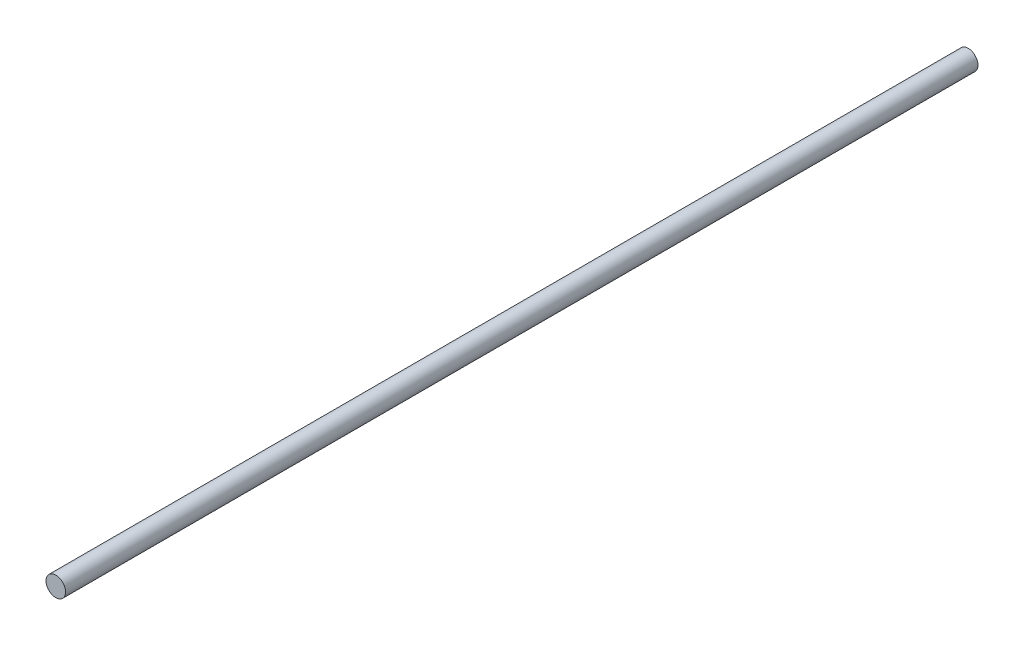
SolidWorks part; units mm, degrees
ref_plane "Front Plane" through (0, 0, 0) normal (0, 0, 1) x (1, 0, 0)
ref_plane "Top Plane" through (0, 0, 0) normal (0, 1, 0) x (1, 0, 0)
ref_plane "Right Plane" through (0, 0, 0) normal (1, 0, 0) x (0, 0, -1)
sketch "Esquisse1" plane through (0, 0, 0) normal (0, 0, 1) x (1, 0, 0)
  circle A0 centre (0, 0) radius 3
  dimension "D1" = 6
extrude "Boss.-Extru.1" add sketch "Esquisse1" along normal blind 280
